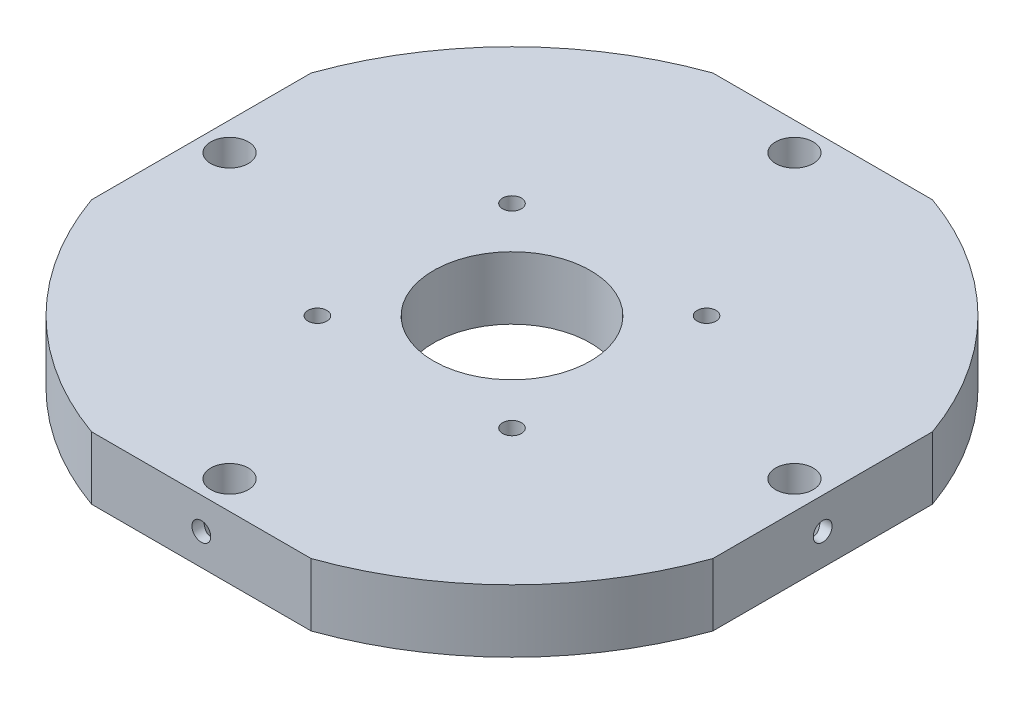
SolidWorks part; units mm, degrees
ref_plane "Front Plane" through (0, 0, 0) normal (0, 0, 1) x (1, 0, 0)
ref_plane "Top Plane" through (0, 0, 0) normal (0, 1, 0) x (1, 0, 0)
ref_plane "Right Plane" through (0, 0, 0) normal (1, 0, 0) x (0, 0, -1)
sketch "Sketch1" plane through (0, 0, 0) normal (0, 1, 0) x (1, 0, 0)
  circle A0 centre (0, 0) radius 52.5
  dimension "D1" = 105
extrude "Boss-Extrude1" add sketch "Sketch1" along normal blind 10
sketch "Sketch3" plane through (0, 10, 0) normal (0, 1, 0) x (1, 0, 0)
  line L0 (0, 45) -> (0, 0) construction
  line L1 (0, 0) -> (0, -45) construction
  circle A0 centre (0, 45) radius 3
  circle A1 centre (45, 0) radius 3
  circle A2 centre (0, -45) radius 3
  circle A3 centre (-45, 0) radius 3
  dimension "D2" = 6
  dimension "D1" = 45
  dimension "D3" = 4
extrude "Cut-Extrude1" cut sketch "Sketch3" against normal through all
sketch "Sketch4" plane through (0, 10, 0) normal (0, 1, 0) x (1, 0, 0)
  line L0 (-17.4929, -49.5) -> (17.4929, -49.5)
  line L1 (0, -52.5) -> (50000, -52.5) construction
  line L2 (49.5, -17.4929) -> (49.5, 17.4929)
  line L3 (17.4929, 49.5) -> (-17.4929, 49.5)
  line L4 (-49.5, 17.4929) -> (-49.5, -17.4929)
  circle A0 centre (0, 0) radius 52.5 construction
  point P4 (0, 0)
  point P7 (0, 0)
  dimension "D1" = 3
  dimension "D2" = 4
extrude "Cut-Extrude-Thin1" cut sketch "Sketch4" against normal through all thin
sketch "Sketch5" plane through (0, 0, 49.5) normal (0, 0, 1) x (1, 0, 0)
  line L0 (-17.4929, 0) -> (17.4929, 0) construction
  line L1 (0, 10) -> (0, 0) construction
  line L2 (-17.4929, 10) -> (17.4929, 10) construction
  circle A0 centre (0, 5) radius 1.5
  point P4 (0, 0)
  dimension "D1" = 3
extrude "Cut-Extrude3" cut sketch "Sketch5" against normal up to next
pattern_circular "CirPattern1" count 4 over 360 about axis through (0, 10, 0) along (0, -1, 0) of "Cut-Extrude3"
sketch "Sketch6" plane through (0, 10, 0) normal (0, 1, 0) x (1, 0, 0)
  circle A0 centre (0, 0) radius 12.5
  dimension "D1" = 25
extrude "Cut-Extrude4" cut sketch "Sketch6" against normal through all
sketch "Sketch7" plane through (0, 10, 0) normal (0, 1, 0) x (1, 0, 0)
  line L0 (0, 49.5) -> (0, -49.5) construction
  line L1 (17.4929, 49.5) -> (-17.4929, 49.5) construction
  line L2 (-17.4929, -49.5) -> (17.4929, -49.5) construction
  line L3 (-49.5, 0) -> (49.5, 0) construction
  line L4 (-49.5, 17.4929) -> (-49.5, -17.4929) construction
  line L5 (49.5, -17.4929) -> (49.5, 17.4929) construction
  circle A0 centre (-15.5, 15.5) radius 1.5
  circle A1 centre (15.5, 15.5) radius 1.5
  circle A2 centre (15.5, -15.5) radius 1.5
  circle A3 centre (-15.5, -15.5) radius 1.5
  dimension "D1" = 3
  dimension "D2" = 15.5
  dimension "D3" = 15.5
extrude "Cut-Extrude5" cut sketch "Sketch7" against normal through all
